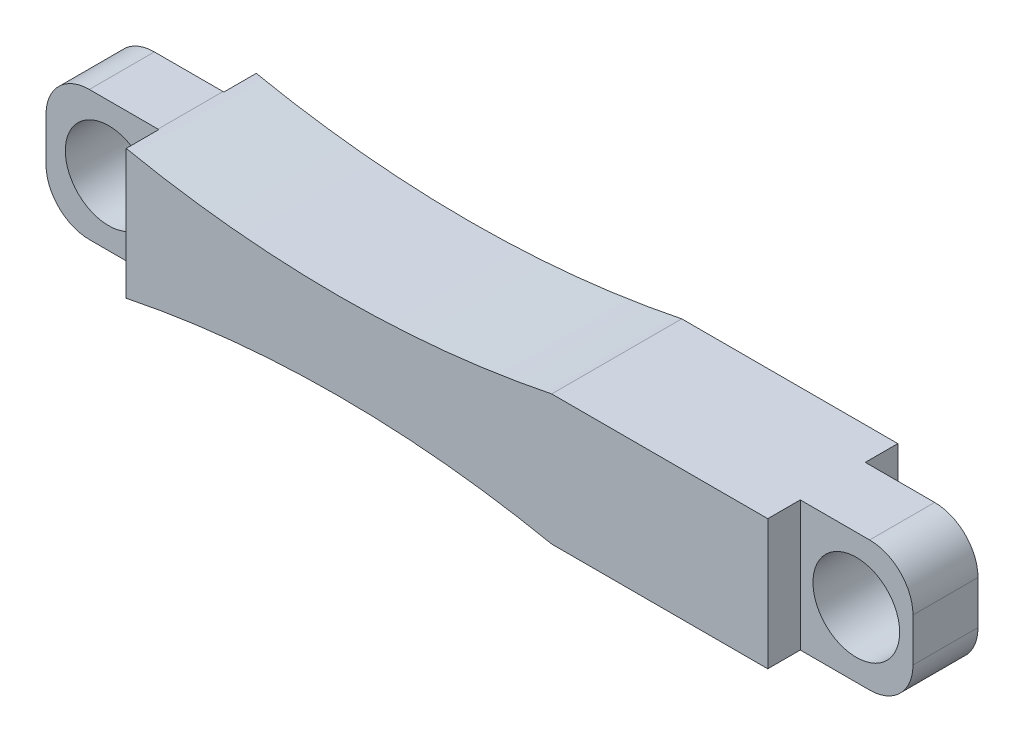
SolidWorks part; units mm, degrees
ref_plane "Front Plane" through (0, 0, 0) normal (0, 0, 1) x (1, 0, 0)
ref_plane "Top Plane" through (0, 0, 0) normal (0, 1, 0) x (1, 0, 0)
ref_plane "Right Plane" through (0, 0, 0) normal (1, 0, 0) x (0, 0, -1)
sketch "Sketch1" plane through (0, 0, 0) normal (0, 0, 1) x (1, 0, 0)
  line L1 (-53.7403, 10.2029) -> (146.2597, 10.2029)
  line L2 (-53.7403, 10.2029) -> (-53.7403, -19.7971)
  line L3 (-53.7403, -19.7971) -> (146.2597, -19.7971)
  line L4 (146.2597, 10.2029) -> (146.2597, -19.7971)
extrude "Boss-Extrude1" add sketch "Sketch1" along normal blind 30
fillet "Fillet1" radius 10 4 edges at (-53.7403, 10.2029, 15) (-53.7403, -19.7971, 15) (146.2597, -19.7971, 15) (146.2597, 10.2029, 15)
sketch "Sketch2" plane through (0, 0, 30) normal (0, 0, 1) x (1, 0, 0)
  line L1 (-27.9011, 10.2029) -> (70.4205, 10.2029)
  line L2 (-27.9011, -19.7971) -> (70.4205, -19.7971)
  line L4 (136.2597, 10.2029) -> (-43.7403, 10.2029) construction
  line L6 (-43.7403, -19.7971) -> (136.2597, -19.7971) construction
  arc A0 (-27.9011, 10.2029) -> (70.4205, 10.2029) centre (21.2597, 249.3814) ccw
  arc A1 (-27.9011, -19.7971) -> (70.4205, -19.7971) centre (21.2597, -259.0413) cw
extrude "Cut-Extrude1" cut sketch "Sketch2" against normal blind 30
sketch "Sketch3" plane through (146.2597, 0, 0) normal (1, 0, 0) x (0, 0, -1)
  line L1 (-30, 10.2029) -> (0, 10.2029) construction
  line L2 (-7.5, 10.2029) -> (0, 10.2029)
  line L3 (0, -19.7971) -> (-30, -19.7971) construction
  line L8 (-7.5, 10.2029) -> (-7.5, -19.7971)
  line L9 (-7.5, -19.7971) -> (0, -19.7971)
  line L10 (0, 10.2029) -> (0, -19.7971)
  line L11 (-22.5, 10.2029) -> (-30, 10.2029)
  line L12 (-22.5, 10.2029) -> (-22.5, -19.7971)
  line L13 (-22.5, -19.7971) -> (-30, -19.7971)
  line L14 (-30, 10.2029) -> (-30, -19.7971)
extrude "Cut-Extrude2" cut sketch "Sketch3" against normal blind 26
sketch "Sketch4" plane through (-53.7403, 0, 0) normal (-1, 0, 0) x (0, 0, 1)
  line L0 (30, -19.7971) -> (30, -9.7971) construction
  line L1 (0, 10.2029) -> (30, 10.2029) construction
  line L2 (22.5, 10.2029) -> (30, 10.2029)
  line L3 (30, -19.7971) -> (0, -19.7971) construction
  line L8 (22.5, 10.2029) -> (22.5, -19.7971)
  line L9 (22.5, -19.7971) -> (30, -19.7971)
  line L10 (30, 10.2029) -> (30, -19.7971)
  line L12 (7.5, 10.2029) -> (0, 10.2029)
  line L13 (7.5, 10.2029) -> (7.5, -19.7971)
  line L14 (7.5, -19.7971) -> (0, -19.7971)
  line L15 (0, 10.2029) -> (0, -19.7971)
extrude "Cut-Extrude3" cut sketch "Sketch4" against normal blind 26
sketch "Sketch5" plane through (0, 0, 30) normal (0, 0, 1) x (1, 0, 0)
  circle A0 centre (-39.2862, -4.7971) radius 10
  circle A1 centre (133.1847, -4.7971) radius 10
  point P0 (133.1847, -4.7971)
extrude "Cut-Extrude4" cut sketch "Sketch5" against normal blind 45
scale "Scale1" scale about centroid uniform scaling yes scale factor 4
